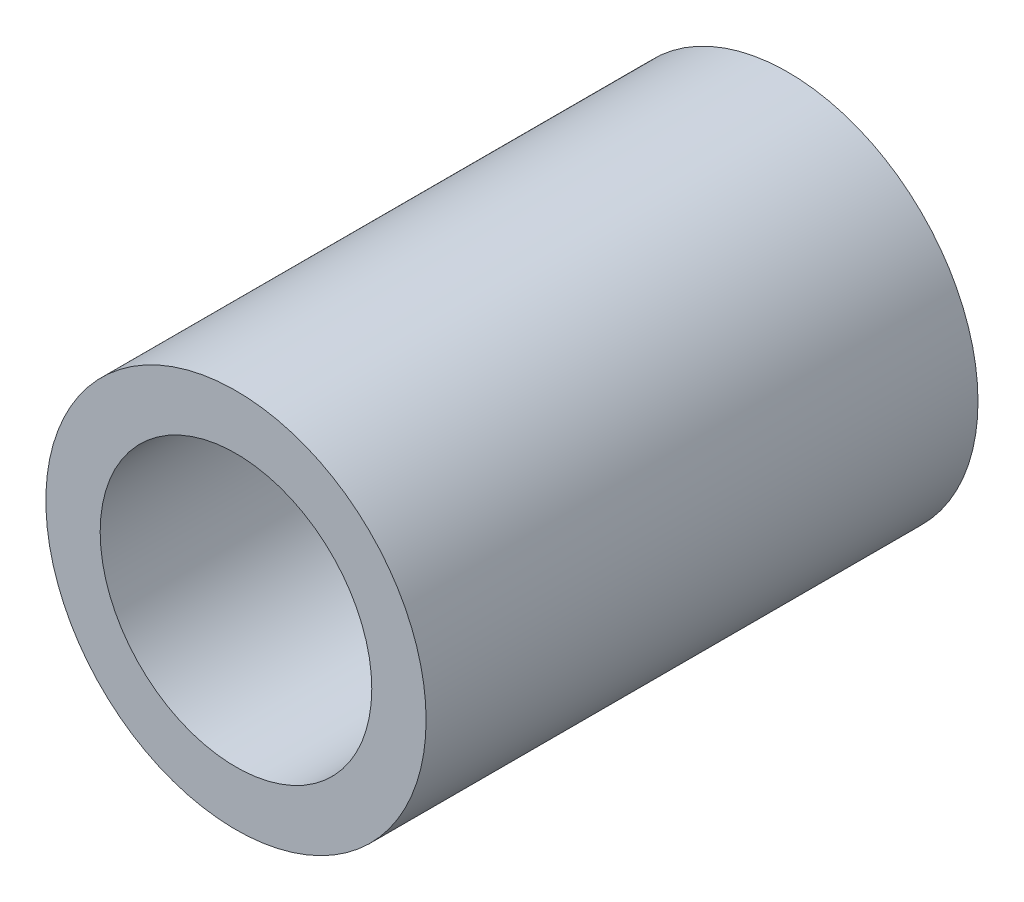
SolidWorks part; units mm, degrees
ref_plane "Alzado" through (0, 0, 0) normal (0, 0, 1) x (1, 0, 0)
ref_plane "Planta" through (0, 0, 0) normal (0, 1, 0) x (1, 0, 0)
ref_plane "Vista lateral" through (0, 0, 0) normal (1, 0, 0) x (0, 0, -1)
sketch "Croquis1" plane through (0, 0, 0) normal (0, 0, 1) x (1, 0, 0)
  circle A0 centre (0, 0) radius 12.5
  circle A1 centre (0, 0) radius 17.5
  dimension "D1" = 25
  dimension "D2" = 35
extrude "Saliente-Extruir1" add sketch "Croquis1" along normal blind 50.8
